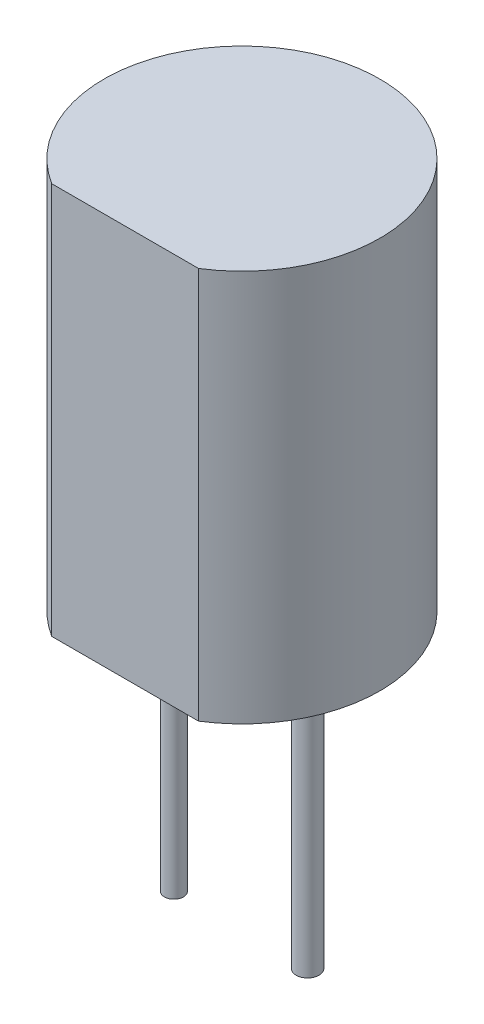
SolidWorks part; units mm, degrees
ref_plane "Front Plane" through (0, 0, 0) normal (0, 0, 1) x (1, 0, 0)
ref_plane "Top Plane" through (0, 0, 0) normal (0, 1, 0) x (1, 0, 0)
ref_plane "Right Plane" through (0, 0, 0) normal (1, 0, 0) x (0, 0, -1)
sketch "Sketch1" plane through (0, 0, 0) normal (0, 1, 0) x (1, 0, 0)
  line L0 (-1.0108, -1.6088) -> (1.0108, -1.6088)
  arc A0 (1.0108, -1.6088) -> (-1.0108, -1.6088) centre (0, 0) ccw
  circle A1 centre (0, 0) radius 1.55
  dimension "D1" = 3.8
  dimension "D2" = 3.1
extrude "Boss-Extrude1" add sketch "Sketch1" along normal blind 5.4 contours A1 | L0 A0 A1
sketch "Sketch2" plane through (0, 0, 0) normal (0, -1, 0) x (1, 0, 0)
  circle A0 centre (0.9046, 0) radius 0.1578
  circle A1 centre (-0.9369, 0) radius 0.1312
extrude "Boss-Extrude2" add sketch "Sketch2" along normal blind 3.81
